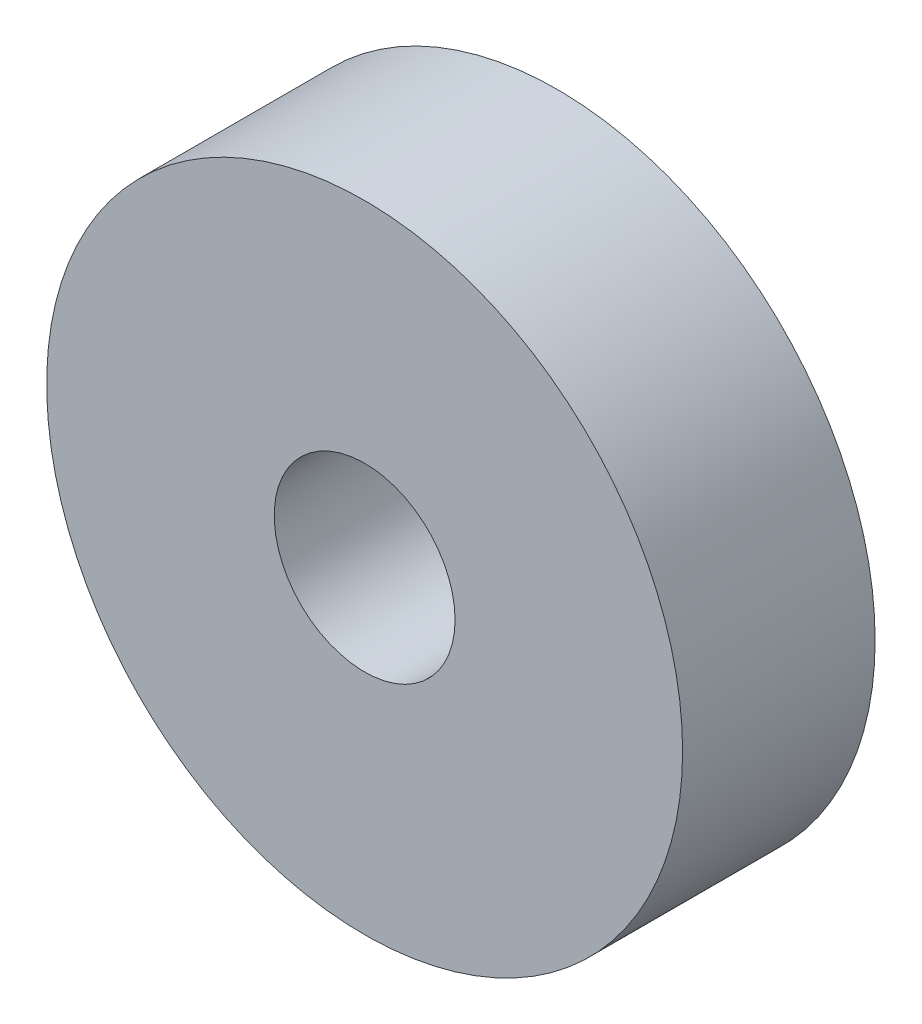
SolidWorks part; units mm, degrees
ref_plane "前视基准面" through (0, 0, 0) normal (0, 0, 1) x (1, 0, 0)
ref_plane "上视基准面" through (0, 0, 0) normal (0, 1, 0) x (1, 0, 0)
ref_plane "右视基准面" through (0, 0, 0) normal (1, 0, 0) x (0, 0, -1)
sketch "草图1" plane through (0, 0, 0) normal (0, 0, 1) x (1, 0, 0)
  circle A0 centre (0, 0) radius 10.9
  dimension "D1" = 21.8
extrude "凸台-拉伸1" add sketch "草图1" along normal blind 6.6
sketch "草图2" plane through (0, 0, 6.6) normal (0, 0, 1) x (1, 0, 0)
  circle A0 centre (0, 0) radius 3.1
  dimension "D1" = 6.2
extrude "切除-拉伸1" cut sketch "草图2" against normal through all
